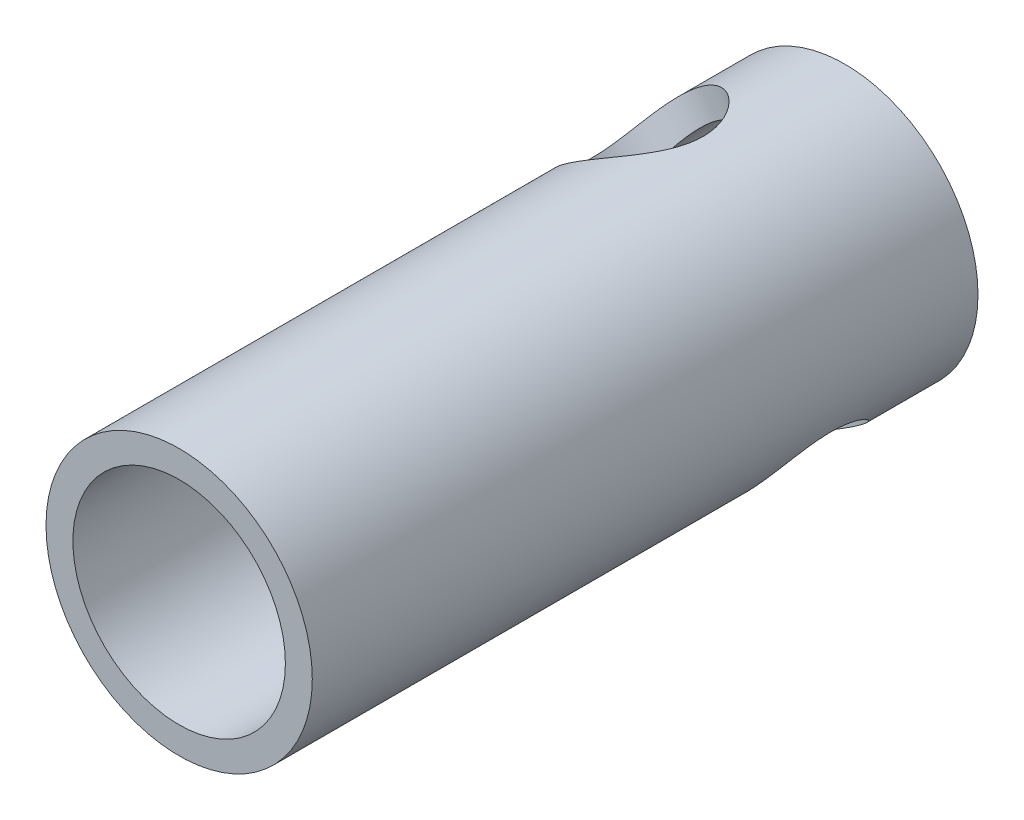
SolidWorks part; units mm, degrees
ref_plane "Alzado" through (0, 0, 0) normal (0, 0, 1) x (1, 0, 0)
ref_plane "Planta" through (0, 0, 0) normal (0, 1, 0) x (1, 0, 0)
ref_plane "Vista lateral" through (0, 0, 0) normal (1, 0, 0) x (0, 0, -1)
sketch "Croquis1" plane through (0, 0, 0) normal (0, 0, 1) x (1, 0, 0)
  circle A0 centre (0, 0) radius 79.8
  circle A1 centre (0, 0) radius 100
  dimension "D1" = 200
  dimension "D2" = 20.2
extrude "Saliente-Extruir1" add sketch "Croquis1" along normal blind 500
sketch "Croquis2" plane through (-136.3943, -90.9157, 0) normal (-0.5538, 0.8326, 0) x (0, 0, 1)
  line L6 (0, 243.7178) -> (0, 84.1178) construction
  circle A1 centre (100, 163.9178) radius 50
  dimension "D1" = 100
  dimension "D2" = 100
extrude "Cortar-Extruir1" cut sketch "Croquis2" against normal through all both and the other way through all
